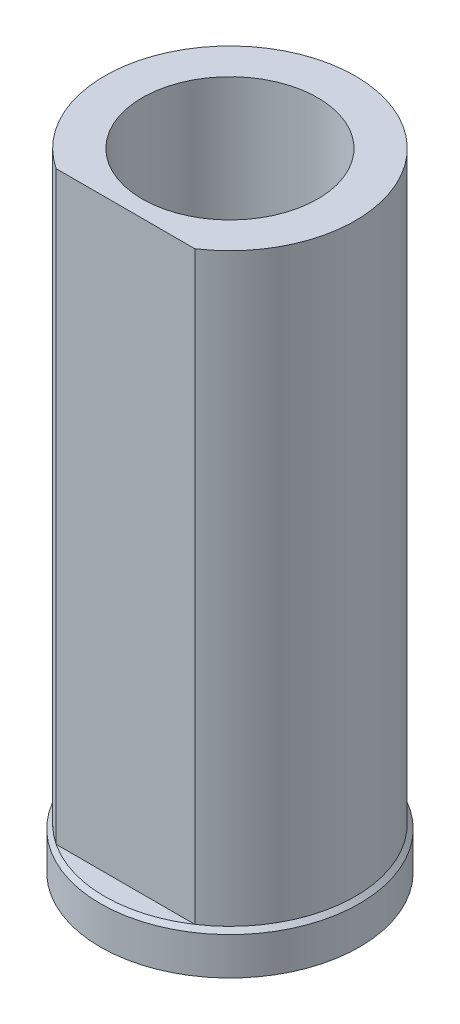
SolidWorks part; units mm, degrees
ref_plane "Alzado" through (0, 0, 0) normal (0, 0, 1) x (1, 0, 0)
ref_plane "Planta" through (0, 0, 0) normal (0, 1, 0) x (1, 0, 0)
ref_plane "Vista lateral" through (0, 0, 0) normal (1, 0, 0) x (0, 0, -1)
sketch "Croquis1" plane through (0, 0, 0) normal (0, 1, 0) x (1, 0, 0)
  circle A0 centre (0, 0) radius 3.1
  dimension "D1" = 6.2
extrude "Saliente-Extruir1" add sketch "Croquis1" along normal blind 1
sketch "Croquis2" plane through (0, 1, 0) normal (0, 1, 0) x (1, 0, 0)
  circle A0 centre (0, 0) radius 3
  dimension "D1" = 6
extrude "Saliente-Extruir2" add sketch "Croquis2" along normal blind 14 separate body
chamfer "Chaflán3" distance 0.1 angle 45 1 edges at (0, 1, 3.1)
sketch "Croquis5" plane through (0, 15, 0) normal (0, 1, 0) x (1, 0, 0)
  line L0 (-1.6583, -2.5) -> (1.6583, -2.5)
  line L1 (0, 3) -> (0, 0) construction
  circle A0 centre (0, 0) radius 3 construction
  point P7 (0, -2.5)
  circle M2 centre (0, 0) radius 3
  dimension "D1" = 5.5
extrude "Cortar-Extruir1" cut sketch "Croquis5" against normal blind 14 and the other way through all contours L0 M2
sketch "Croquis6" plane through (0, 15, 0) normal (0, 1, 0) x (1, 0, 0)
  circle A0 centre (0, 0) radius 2.1
  dimension "D1" = 4.2
extrude "Cortar-Extruir2" cut sketch "Croquis6" against normal blind 14
